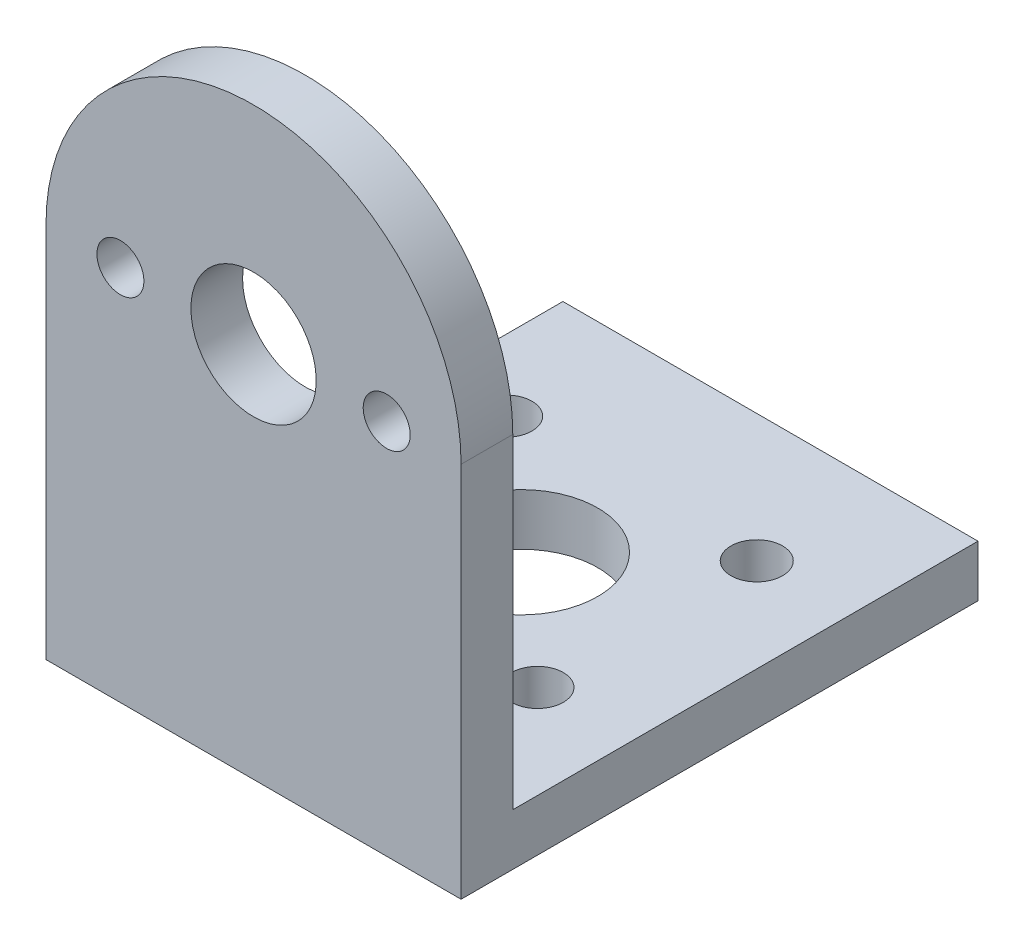
SolidWorks part; units mm, degrees
ref_plane "前视基准面" through (0, 0, 0) normal (0, 0, 1) x (1, 0, 0)
ref_plane "上视基准面" through (0, 0, 0) normal (0, 1, 0) x (1, 0, 0)
ref_plane "右视基准面" through (0, 0, 0) normal (1, 0, 0) x (0, 0, -1)
sketch "草图1" plane through (0, 0, 0) normal (0, 1, 0) x (1, 0, 0)
  line L0 (12.5256, 36.2851) -> (12.5256, -3.8746) construction
  line L1 (0, 0) -> (26.5, 0)
  line L2 (0, 0) -> (0, 33)
  line L3 (0, 33) -> (26.5, 33)
  line L4 (26.5, 0) -> (26.5, 33)
  circle A0 centre (12.5256, 17.8) radius 4.9
  circle A1 centre (4.5256, 24.85) radius 1.65
  circle A2 centre (20.5256, 24.85) radius 1.65
  circle A3 centre (4.5256, 10.85) radius 1.65
  circle A4 centre (20.5256, 10.85) radius 1.65
  dimension "D4" = 9.8
  dimension "D5" = 3.3
  dimension "D1" = 26.5
  dimension "D2" = 33
  dimension "D3" = 15.2
  dimension "D6" = 8.15
  dimension "D7" = 14
  dimension "D8" = 16
  dimension "D9" = 16
  dimension "D10" = 12.5256
extrude "凸台-拉伸1" add sketch "草图1" along normal blind 3.3
sketch "草图2" plane through (0, 3.3, 0) normal (0, 1, 0) x (1, 0, 0)
  line L0 (0, 33) -> (0, 0) construction
  line L1 (0, 3.3) -> (26.5, 3.3)
  line L2 (0, 3.3) -> (0, 0)
  line L3 (0, 0) -> (26.5, 0)
  line L4 (26.5, 3.3) -> (26.5, 0)
  dimension "D1" = 3.3
extrude "凸台-拉伸2" add sketch "草图2" along normal blind 34
sketch "草图3" plane through (0, 0, -3.3) normal (0, 0, -1) x (-1, 0, 0)
  line L0 (-26.5, 37.3) -> (-26.5, 3.3) construction
  line L1 (0, 3.3) -> (-26.5, 3.3)
  line L2 (0, 3.3) -> (0, 24.05)
  line L3 (0, 24.05) -> (-26.5, 24.05)
  line L4 (-26.5, 3.3) -> (-26.5, 24.05)
  line L6 (-26.5, 24.05) -> (0, 24.05)
  line L7 (-26.5, 24.05) -> (-26.5, 37.3)
  line L8 (-26.5, 37.3) -> (0, 37.3)
  line L9 (0, 24.05) -> (0, 37.3)
  arc A0 (0, 24.05) -> (-26.5, 24.05) centre (-13.25, 24.05) ccw
  line M3 (0, 3.3) -> (0, 37.3)
  line M4 (0, 37.3) -> (-26.5, 37.3)
  line M5 (-26.5, 37.3) -> (-26.5, 3.3)
  dimension "D1" = 20.75
extrude "切除-拉伸3" cut sketch "草图3" against normal blind 34 contours A0 L8 M5 | A0 M3 M4
sketch "草图4" plane through (0, 0, -3.3) normal (0, 0, -1) x (-1, 0, 0)
  line L0 (-13.25, 39.1804) -> (-13.25, 4.0985) construction
  circle A0 centre (-13.25, 24.05) radius 4
  arc A1 (0, 24.05) -> (-26.5, 24.05) centre (-13.25, 24.05) ccw construction
  circle A2 centre (-4.75, 24.05) radius 1.5
  circle A3 centre (-21.75, 24.05) radius 1.5
  dimension "D2" = 3
  dimension "D3" = 8
  dimension "D1" = 17
extrude "切除-拉伸4" cut sketch "草图4" against normal blind 34 contours A0 | A2 | A3
